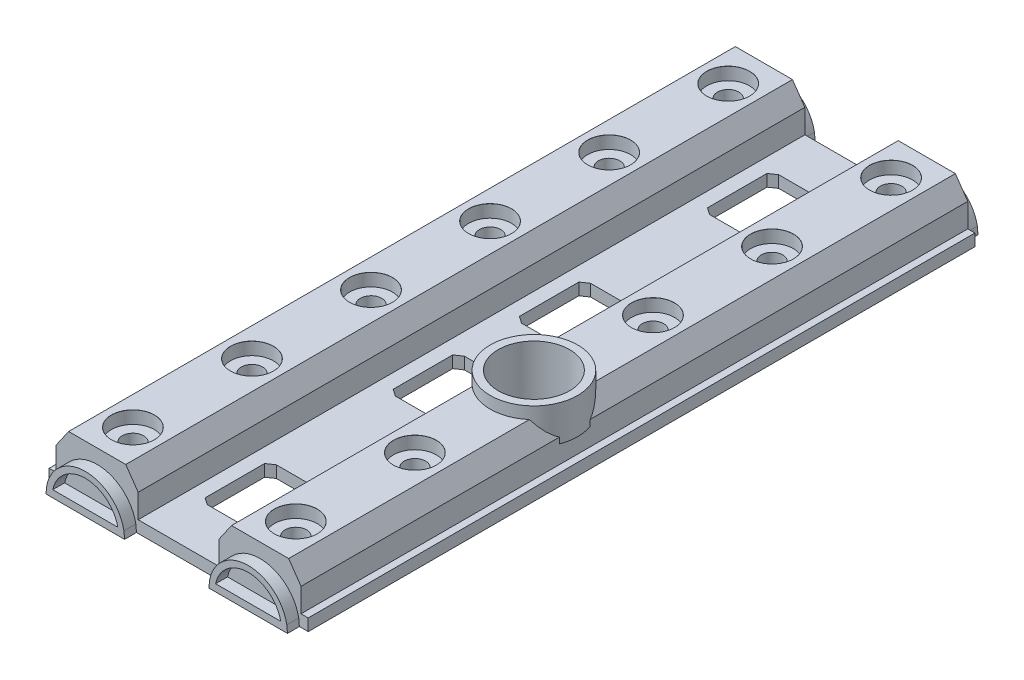
SolidWorks part; units mm, degrees
ref_plane "Front Plane" through (0, 0, 0) normal (0, 0, 1) x (1, 0, 0)
ref_plane "Top Plane" through (0, 0, 0) normal (0, 1, 0) x (1, 0, 0)
ref_plane "Right Plane" through (0, 0, 0) normal (1, 0, 0) x (0, 0, -1)
sketch "Sketch4" plane through (0, 0, 0) normal (0, 0, 1) x (1, 0, 0)
  line L0 (-107.2791, 0) -> (103.0685, 0) construction
  line L1 (-21.4951, 53.6169) -> (-21.4951, -60.985) construction
  line L2 (-41.7029, 2.5) -> (-38.7029, 2.5)
  line L3 (-41.7029, -2.5) -> (-41.7029, 2.5)
  line L4 (-38.7029, 2.5) -> (-38.7029, 12.5)
  line L5 (-41.7029, -2.5) -> (-1.2874, -2.5)
  line L6 (-9.4951, 20) -> (-33.4951, 20)
  line L7 (-33.4951, 20) -> (-38.7029, 12.5)
  line L8 (-9.4951, 20) -> (-4.2874, 12.5)
  line L9 (-4.2874, 2.5) -> (-4.2874, 12.5)
  line L10 (-1.2874, 2.5) -> (26.7126, 2.5)
  line L11 (-1.2874, 2.5) -> (-4.2874, 2.5)
  line L12 (-1.2874, -2.5) -> (26.7126, -2.5)
  line L13 (12.7126, 34.1366) -> (12.7126, -19.1686) construction
  line L14 (26.7126, 2.5) -> (29.7126, 2.5)
  line L15 (29.7126, 2.5) -> (29.7126, 12.5)
  line L16 (34.9203, 20) -> (29.7126, 12.5)
  line L17 (58.9203, 20) -> (64.128, 12.5)
  line L18 (34.9203, 20) -> (58.9203, 20)
  line L19 (67.128, -2.5) -> (26.7126, -2.5)
  line L20 (64.128, 2.5) -> (64.128, 12.5)
  line L21 (67.128, -2.5) -> (67.128, 2.5)
  line L22 (67.128, 2.5) -> (64.128, 2.5)
  point P14 (-21.4951, 20)
  point P15 (-21.4951, -2.5)
  point P22 (12.7126, -2.5)
  point P24 (12.7126, 2.5)
  point P31 (46.9203, -2.5)
  point P32 (46.9203, 20)
extrude "Boss-Extrude1" add sketch "Sketch4" against normal blind 280
sketch "Sketch5" plane through (0, 0, 0) normal (0, 0, 1) x (1, 0, 0)
  line L0 (-41.7029, -2.5) -> (67.128, -2.5) construction
  line L1 (-37.9951, -2.5) -> (-4.9951, -2.5)
  line L2 (-4.9951, -2.5) -> (-5.2679, 0.4876)
  line L3 (-37.7224, 0.4876) -> (-5.2679, 0.4876)
  line L4 (-37.7224, 0.4876) -> (-37.9951, -2.5)
  line L5 (-4.9951, -2.5) -> (-37.9951, -2.5)
  arc A0 (-4.9951, -2.5) -> (-37.9951, -2.5) centre (-21.4951, -2.5) ccw
  arc A1 (-7.8176, 0.4876) -> (-35.1727, 0.4876) centre (-21.4951, -2.5) ccw
  line M5 (-41.7029, -2.5) -> (67.128, -2.5)
extrude "Boss-Extrude3" add sketch "Sketch5" along normal blind 5 contours A1 L3 A0 | L3 L4 L2 M5
sketch "Sketch7" plane through (0, 2.5, 0) normal (0, 1, 0) x (1, 0, 0)
  line L0 (12.7126, 280) -> (12.7126, 0) construction
  line L1 (29.7126, 280) -> (-4.2874, 280) construction
  line L2 (29.7126, 0) -> (-4.2874, 0) construction
  line L3 (-41.7029, 140) -> (64.128, 140) construction
  line L4 (-41.7029, 280) -> (-41.7029, 0) construction
  line L5 (64.128, 280) -> (64.128, 0) construction
ref_plane "Plane1" through (12.7126, 0, 0) normal (-1, 0, 0) x (0, 0, 1)
mirror "Mirror1" about plane through (12.7126, 0, 0) normal (-1, 0, 0) of "Boss-Extrude3"
ref_plane "Plane2" through (0, 0, -140) normal (0, 0, 1) x (1, 0, 0)
mirror "Mirror2" about plane through (0, 0, -140) normal (0, 0, 1) of "Mirror1", "Boss-Extrude3"
sketch "Sketch8" plane through (0, 20, 0) normal (0, 1, 0) x (1, 0, 0)
  line L0 (46.9203, 280) -> (46.9203, 0) construction
  line L1 (58.9203, 280) -> (34.9203, 280) construction
  line L2 (58.9203, 0) -> (34.9203, 0) construction
  line L3 (46.9203, 280) -> (46.9203, 265)
  line L4 (46.9203, 265) -> (46.9203, 215)
  line L5 (46.9203, 215) -> (46.9203, 165)
  line L6 (46.9203, 165) -> (46.9203, 115)
  line L7 (46.9203, 115) -> (46.9203, 65)
  line L8 (46.9203, 65) -> (46.9203, 15)
  circle A0 centre (46.9203, 265) radius 8
  circle A1 centre (46.9203, 215) radius 8
  circle A2 centre (46.9203, 165) radius 8
  circle A3 centre (46.9203, 115) radius 8
  circle A4 centre (46.9203, 65) radius 8
  circle A5 centre (46.9203, 15) radius 8
hole_wizard "CBORE SLOT for M8 Hex Head Bolt1" positions "Sketch11" profile "Sketch10" size "M8" standard "ISO" slot yes
sketch "Sketch11" plane through (0, 20, 0) normal (0, 1, 0) x (1, 0, 0)
  point P0 (46.9203, 265)
  point P3 (46.9203, 215)
  point P6 (46.9203, 165)
  point P9 (46.9203, 115)
  point P12 (46.9203, 65)
  point P15 (46.9203, 15)
sketch "Sketch10" plane through (46.9203, 20, -265) normal (1, 0, 0) x (0, 0, 1)
  line L0 (0, 0) -> (0, 34.5439)
  line L1 (0, 34.5439) -> (4.5, 31.84)
  line L2 (4.5, 31.84) -> (4.5, 5.3)
  line L3 (4.5, 5.3) -> (9.0055, 5.3)
  line L5 (9.0055, 5.3) -> (9.0055, 0.025)
  line L6 (9.0055, 0.025) -> (9.0305, 0)
  line L7 (9.0305, 0) -> (0, 0)
  line L8 (-9.0055, 0.025) -> (-9.0305, 0) construction
  line L10 (0, 34.5439) -> (-4.5, 31.84) construction
  line L11 (0, -6.35) -> (0, 107.95) construction
  dimension "Hole Dia." = 9
  dimension "Hole Depth" = 31.84
  dimension "C'Bore Dia." = 18.011
  dimension "C'Bore Depth" = 5.3
  dimension "Near C'Sink Dia." = 18.061
  dimension "Near C'Sink Angle" = 90
  dimension "Drill Angle" = 118
mirror "Mirror3" about plane through (12.7126, 0, 0) normal (-1, 0, 0) of "CBORE SLOT for M8 Hex Head Bolt1"
sketch "Sketch12" plane through (0, 20, 0) normal (0, 1, 0) x (1, 0, 0)
  circle A0 centre (46.9203, 115) radius 18.3735
extrude "Boss-Extrude4" add sketch "Sketch12" along normal blind 5 and the other way blind 10
sketch "Sketch14" plane through (0, 25, 0) normal (0, 1, 0) x (1, 0, 0)
  circle A0 centre (46.9203, 115) radius 15
extrude "Cut-Extrude1" cut sketch "Sketch14" against normal blind 28
sketch "Sketch16" plane through (0, 2.5, 0) normal (0, 1, 0) x (1, 0, 0)
  line L1 (20.7126, 20) -> (4.7126, 20)
  line L4 (20.7126, 49) -> (4.7126, 49)
  line L5 (1.8026, 47) -> (4.7126, 49)
  line L6 (1.8026, 22) -> (4.7126, 20)
  line L7 (1.8026, 47) -> (1.8026, 22)
  line L8 (23.6226, 47) -> (23.6226, 22)
  line L9 (23.6226, 22) -> (20.7126, 20)
  line L10 (23.6226, 47) -> (20.7126, 49)
  line L13 (23.6226, 101) -> (20.7126, 99)
  line L14 (23.6226, 126) -> (20.7126, 128)
  line L15 (23.6226, 101) -> (23.6226, 126)
  line L16 (1.8026, 101) -> (1.8026, 126)
  line L17 (1.8026, 126) -> (4.7126, 128)
  line L18 (1.8026, 101) -> (4.7126, 99)
  line L19 (20.7126, 99) -> (4.7126, 99)
  line L20 (20.7126, 128) -> (4.7126, 128)
extrude "Cut-Extrude2" cut sketch "Sketch16" against normal through all
mirror "Mirror4" about plane through (0, 0, -140) normal (0, 0, 1) of "Cut-Extrude2"
